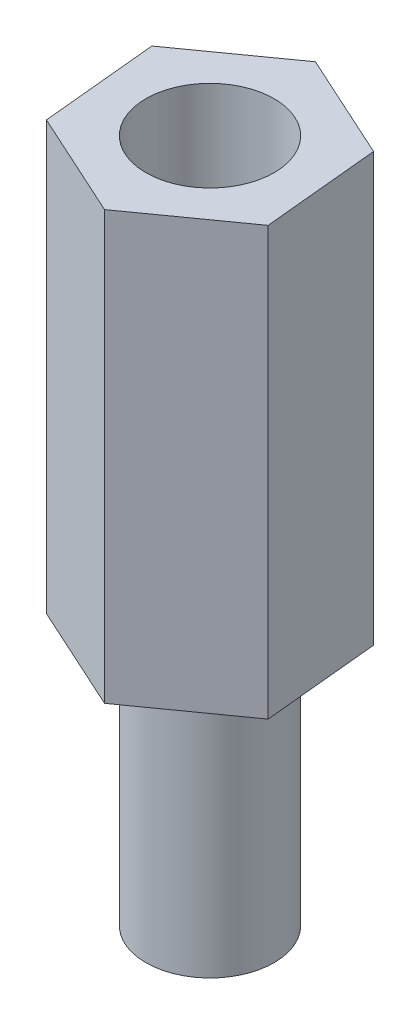
SolidWorks part; units mm, degrees
ref_plane "前视基准面" through (0, 0, 0) normal (0, 0, 1) x (1, 0, 0)
ref_plane "上视基准面" through (0, 0, 0) normal (0, 1, 0) x (1, 0, 0)
ref_plane "右视基准面" through (0, 0, 0) normal (1, 0, 0) x (0, 0, -1)
sketch "草图1" plane through (0, 0, 0) normal (0, 1, 0) x (1, 0, 0)
  circle A0 centre (0, 0) radius 1.5
  dimension "D1" = 3
extrude "凸台-拉伸1" add sketch "草图1" along normal blind 6
sketch "草图2" plane through (0, 6, 0) normal (0, 1, 0) x (1, 0, 0)
  line L1 (2.4958, -1.1366) -> (2.2322, 1.5931)
  line L2 (2.2322, 1.5931) -> (-0.2636, 2.7297)
  line L3 (-0.2636, 2.7297) -> (-2.4958, 1.1366)
  line L4 (-2.4958, 1.1366) -> (-2.2322, -1.5931)
  line L5 (-2.2322, -1.5931) -> (0.2636, -2.7297)
  line L6 (0.2636, -2.7297) -> (2.4958, -1.1366)
  circle A0 centre (0, 0) radius 2.375 construction
  dimension "D1" = 4.75
extrude "凸台-拉伸2" add sketch "草图2" along normal blind 10
sketch "草图3" plane through (0, 16, 0) normal (0, 1, 0) x (1, 0, 0)
  circle A0 centre (0, 0) radius 1.5
  dimension "D1" = 3
extrude "切除-拉伸1" cut sketch "草图3" against normal blind 5
